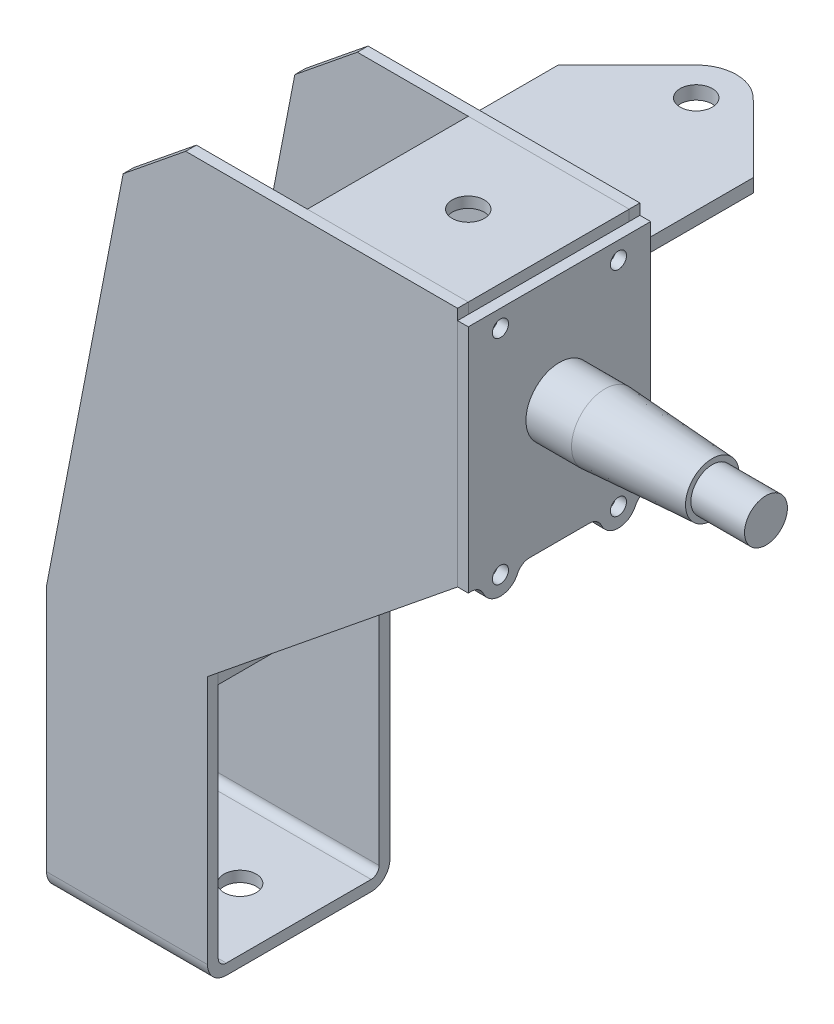
SolidWorks part; units mm, degrees
ref_plane "Front Plane" through (0, 0, 0) normal (0, 0, 1) x (1, 0, 0)
ref_plane "Top Plane" through (0, 0, 0) normal (0, 1, 0) x (1, 0, 0)
ref_plane "Right Plane" through (0, 0, 0) normal (1, 0, 0) x (0, 0, -1)
sketch "Sketch1" plane through (0, 0, 0) normal (0, 0, 1) x (1, 0, 0)
  line L0 (0, 0) -> (0, -100)
  line L1 (0, -2.2) -> (0, 2.2) construction
  line L2 (0, 0) -> (93.2275, 75.5556)
  line L3 (93.2275, 75.5556) -> (93.2275, 165.5556)
  line L4 (0, -100) -> (-60, -100)
  line L5 (-60, -100) -> (-60, -0.5906)
  line L6 (-60, -0.5906) -> (-31.4466, 146.6667)
  line L7 (-31.4466, 146.6667) -> (-8.1397, 165.5556)
  line L8 (-8.1397, 165.5556) -> (93.2275, 165.5556)
  point P0 (0, 0)
  dimension "D1" = 100
  dimension "D2" = 120
  dimension "D3" = 90
  dimension "D4" = 60
  dimension "D5" = 90
  dimension "D6" = 30
  dimension "D7" = 150
  dimension "D8" = 150
  dimension "D9" = 190
  dimension "D10" = 101.3672
  dimension "D11" = 129.023
  dimension "D12" = 99.4094
sketch "Sketch3" plane through (0, 0, 0) normal (1, 0, 0) x (0, 0, -1)
  line L2 (93.1124, 165.5556) -> (89.1124, 165.5556)
  line L3 (89.1124, 165.5556) -> (89.1124, -93)
  line L4 (86.1124, -96) -> (32.1124, -96)
  line L5 (0, 146.6667) -> (0, 165.5556) construction
  line L6 (0, 75.5556) -> (0, 165.5556) construction
  line L7 (0, -100) -> (0, -0.5906) construction
  line L8 (0, 84.2751) -> (0, -84.2751) construction
  line L9 (29.1124, -93) -> (29.1124, 165.5556)
  line L10 (29.1124, 165.5556) -> (25.1124, 165.5556)
  line L12 (93.1124, 161.5556) -> (93.1124, 161.5556)
  line L13 (93.1124, 165.5556) -> (93.1124, -93)
  line L14 (86.1124, -100) -> (32.1124, -100)
  line L15 (25.1124, -93) -> (25.1124, 168.1451)
  line L16 (25.1124, 161.5556) -> (25.1124, 161.5556)
  line L17 (93.1124, 161.5556) -> (93.1124, -93) construction
  line L18 (25.1124, -93) -> (25.1124, 161.5556) construction
  arc A0 (32.1124, -96) -> (29.1124, -93) centre (32.1124, -93) cw
  arc A1 (89.1124, -93) -> (86.1124, -96) centre (86.1124, -93) cw
  arc A2 (93.1124, -93) -> (86.1124, -100) centre (86.1124, -93) cw
  arc A3 (32.1124, -100) -> (25.1124, -93) centre (32.1124, -93) cw
  point P2 (0, 165.5556)
  point P7 (0, -100)
  point P20 (29.1124, -96)
  point P23 (89.1124, -96)
  dimension "D6" = 3
  dimension "D1" = 4
  dimension "D5" = 60
extrude "Boss-Extrude2" add sketch "Sketch3" along normal mid plane 214 contours A3 L14 A2 L13 L2 L3 A1 L4 A0 L9 L10 L15
sketch "Sketch4" plane through (0, 0, 0) normal (0, 0, 1) x (1, 0, 0)
  line L8 (-190, 11.8967) -> (-190, -230)
  line L9 (-190, -230) -> (130, -230)
  line L10 (130, -230) -> (130, -61.9751)
  line L11 (130, -61.9751) -> (223.2275, 13.5805)
  line L12 (223.2275, 13.5805) -> (223.2275, 295.5556)
  line L13 (223.2275, 295.5556) -> (-54.2043, 295.5556)
  line L14 (-54.2043, 295.5556) -> (-150.0618, 217.8685)
  line L15 (-150.0618, 217.8685) -> (-190, 11.8967)
  line L16 (-60, -0.5906) -> (-60, -100)
  line L17 (-60, -100) -> (0, -100)
  line L18 (0, -100) -> (0, 0)
  line L19 (0, 0) -> (93.2275, 75.5556)
  line L20 (93.2275, 75.5556) -> (93.2275, 165.5556)
  line L21 (93.2275, 165.5556) -> (-8.1397, 165.5556)
  line L22 (-8.1397, 165.5556) -> (-31.4466, 146.6667)
  line L23 (-31.4466, 146.6667) -> (-60, -0.5906)
  line L24 (-60, -0.5906) -> (-60, -100)
  line L25 (-60, -100) -> (0, -100)
  line L26 (0, -100) -> (0, 0)
  line L27 (0, 0) -> (93.2275, 75.5556)
  line L28 (93.2275, 75.5556) -> (93.2275, 165.5556)
  line L29 (93.2275, 165.5556) -> (-8.1397, 165.5556)
  line L30 (-8.1397, 165.5556) -> (-31.4466, 146.6667)
  line L31 (-31.4466, 146.6667) -> (-60, -0.5906)
  dimension "D1" = 0
  dimension "D2" = 130
extrude "Cut-Extrude1" cut sketch "Sketch4" against normal blind 214
sketch "Sketch5" plane through (0, 0, 0) normal (1, 0, 0) x (0, 0, -1)
  line L0 (89.1124, 0) -> (89.1124, -93) construction
  line L1 (29.1124, -0.5906) -> (89.1124, -0.5906)
  line L2 (29.1124, -0.5906) -> (29.1124, -4.5906)
  line L3 (29.1124, -4.5906) -> (89.1124, -4.5906)
  line L4 (89.1124, -0.5906) -> (89.1124, -4.5906)
  dimension "D1" = 4
  dimension "D2" = 60
extrude "Boss-Extrude3" add sketch "Sketch5" against normal blind 60 separate body
sketch "Sketch6" plane through (93.2275, 0, 0) normal (1, 0, 0) x (0, 0, -1)
  line L0 (89.1124, 165.5556) -> (89.1124, 75.5556) construction
  line L1 (29.1124, 165.5556) -> (89.1124, 165.5556)
  line L2 (29.1124, 165.5556) -> (29.1124, 161.5556)
  line L3 (29.1124, 161.5556) -> (89.1124, 161.5556)
  line L4 (89.1124, 165.5556) -> (89.1124, 161.5556)
  dimension "D1" = 4
extrude "Boss-Extrude4" add sketch "Sketch6" against normal blind 60 separate body
sketch "Sketch7" plane through (93.2275, 0, 0) normal (1, 0, 0) x (0, 0, -1)
  line L0 (25.1124, 161.5556) -> (93.1124, 161.5556)
  line L2 (25.1124, 161.5556) -> (25.1124, 75.5556)
  line L3 (25.1124, 75.5556) -> (26.2037, 75.5556)
  line L4 (93.1124, 161.5556) -> (93.1124, 75.5556)
  line L5 (29.1124, 0) -> (29.1124, 75.5556) construction
  line L6 (89.1124, 75.5556) -> (89.1124, 0) construction
  line L7 (29.1124, 75.5556) -> (29.1124, 165.5556) construction
  line L8 (89.1124, 165.5556) -> (89.1124, 75.5556) construction
  line L9 (48.0211, 75.5556) -> (70.2037, 75.5556)
  line L10 (92.0211, 75.5556) -> (93.1124, 75.5556)
  arc A0 (74.749, 72.6389) -> (87.4758, 72.6389) centre (81.1124, 75.5556) ccw
  arc A1 (30.749, 72.6389) -> (43.4758, 72.6389) centre (37.1124, 75.5556) ccw
  circle A2 centre (37.1124, 155.0821) radius 3
  circle A3 centre (81.1124, 155.0821) radius 3
  arc A4 (30.749, 72.6389) -> (26.2037, 75.5556) centre (26.2037, 70.5556) ccw
  arc A5 (43.4758, 72.6389) -> (48.0211, 75.5556) centre (48.0211, 70.5556) cw
  arc A6 (74.749, 72.6389) -> (70.2037, 75.5556) centre (70.2037, 70.5556) ccw
  arc A7 (87.4758, 72.6389) -> (92.0211, 75.5556) centre (92.0211, 70.5556) cw
  circle A8 centre (37.1124, 75.5556) radius 3
  circle A9 centre (81.1124, 75.5556) radius 3
  point P28 (44.1124, 75.5556)
  point P33 (88.1124, 75.5556)
  dimension "D1" = 14
  dimension "D2" = 14
  dimension "D3" = 6
  dimension "D4" = 6
  dimension "D5" = 8
  dimension "D6" = 8
  dimension "D7" = 79.5266
  dimension "D8" = 8
  dimension "D9" = 8
  dimension "D10" = 44
  dimension "D11" = 5
  dimension "D12" = 5
  dimension "D13" = 5
  dimension "D14" = 5
  dimension "D15" = 6
  dimension "D16" = 6
extrude "Boss-Extrude5" add sketch "Sketch7" along normal blind 4 separate body
sketch "Sketch8" plane through (0, 0, -93.1124) normal (0, 0, -1) x (-1, 0, 0)
  line L1 (12.1021, 115) -> (-60.6218, 115)
  line L2 (12.1021, 115) -> (12.1021, 120)
  line L3 (12.1021, 120) -> (-60.6218, 120)
  line L4 (-60.6218, 115) -> (-60.6218, 120)
  line L5 (12.1021, 117.5) -> (37.1021, 117.5)
  line L7 (60, -0.5906) -> (31.4466, 146.6667) construction
  point P8 (60, -0.5906)
  dimension "D1" = 5
  dimension "D2" = 115
  dimension "D3" = 130
  dimension "D4" = 167.0653
  dimension "D5" = 115.635
  dimension "D6" = 25
extrude "Boss-Extrude6" add sketch "Sketch8" along normal blind 100 separate body contours L4 L1 L2 L3
chamfer "Chamfer1" distance 25 angle 45 1 edges at (-12.1021, 117.5, -193.1124)
chamfer "Chamfer2" distance 25 angle 45 1 edges at (60.6218, 117.5, -193.1124)
sketch "Sketch9" plane through (0, 115, 0) normal (0, -1, 0) x (1, 0, 0)
  line L2 (93.2275, -93.1124) -> (0, -93.1124) construction
  line L3 (60.6218, -168.1124) -> (60.6218, -93.1124) construction
  circle A1 centre (24.2218, -183.1124) radius 15
  dimension "D1" = 30
  dimension "D3" = 36.4
  dimension "D2" = 90
extrude "Boss-Extrude7" add sketch "Sketch9" against normal blind 5
sketch "Sketch10" plane through (97.2275, 0, 0) normal (1, 0, 0) x (0, 0, -1)
  line L0 (25.1124, 165.5556) -> (93.1124, 75.5556)
  circle A0 centre (59.1124, 120.5556) radius 12.25
  point P6 (0, 0)
  dimension "D1" = 24.5
extrude "Cut-Extrude2" cut sketch "Sketch10" against normal blind 4
sketch "Sketch12" plane through (0, 165.5556, 0) normal (0, 1, 0) x (1, 0, 0)
  line L0 (33.2275, 89.1124) -> (93.2275, 29.1124)
  circle A0 centre (63.2275, 59.1124) radius 6
  dimension "D1" = 12
extrude "Cut-Extrude5" cut sketch "Sketch12" against normal blind 8 contours L0 A0 | L0 A0
sketch "Sketch13" plane through (0, -100, 0) normal (0, -1, 0) x (1, 0, 0)
  circle A0 centre (-23.1606, -60.4397) radius 6
extrude "Cut-Extrude6" cut sketch "Sketch13" against normal blind 10
sketch "Sketch15" plane through (93.2275, 0, 0) normal (-1, 0, 0) x (0, 0, 1)
  circle A0 centre (-59.1124, 120.5556) radius 15
  dimension "D1" = 30
extrude "Boss-Extrude8" add sketch "Sketch15" along normal blind 10 separate body
sketch "Sketch16" plane through (97.2275, 0, 0) normal (1, 0, 0) x (0, 0, -1)
  circle A0 centre (59.1124, 120.5556) radius 12.25
extrude "Boss-Extrude9" add sketch "Sketch16" against normal blind 10 separate body
sketch "Sketch17" plane through (97.2275, 0, 0) normal (1, 0, 0) x (0, 0, -1)
  circle A0 centre (59.1124, 120.5556) radius 12.5
  dimension "D1" = 25
extrude "Boss-Extrude10" add sketch "Sketch17" along normal blind 77 separate body
sketch "Sketch18" plane through (174.2275, 0, 0) normal (1, 0, 0) x (0, 0, -1)
  circle A0 centre (59.1124, 120.5556) radius 8
  circle A1 centre (59.1124, 120.5556) radius 12.5
  dimension "D1" = 16
  dimension "D2" = 25
extrude "Cut-Extrude7" cut sketch "Sketch18" against normal blind 20
chamfer "Chamfer3" distance 40 distance2 2.5 1 edges at (154.2275, 120.5556, -71.6124)
combine bodies "Combine1" operation type add bodies to combine 116 114 113
sketch "Sketch19" plane through (0, 115, 0) normal (0, -1, 0) x (1, 0, 0)
  circle A0 centre (24.2218, -183.1124) radius 6
  dimension "D1" = 12
extrude "Cut-Extrude8" cut sketch "Sketch19" against normal blind 20
